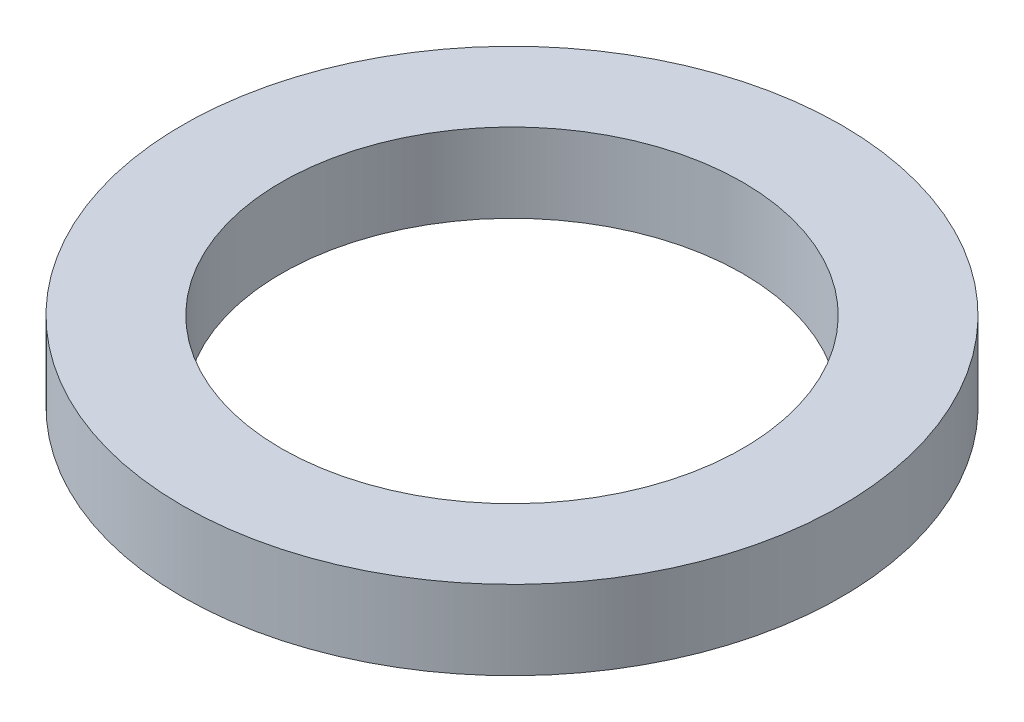
SolidWorks part; units mm, degrees
ref_plane "Alzado" through (0, 0, 0) normal (0, 0, 1) x (1, 0, 0)
ref_plane "Planta" through (0, 0, 0) normal (0, 1, 0) x (1, 0, 0)
ref_plane "Vista lateral" through (0, 0, 0) normal (1, 0, 0) x (0, 0, -1)
sketch "Croquis1" plane through (0, 0, 0) normal (0, 1, 0) x (1, 0, 0)
  circle A0 centre (0, 0) radius 1.75
  circle A1 centre (0, 0) radius 2.5
  dimension "D1" = 3.5
  dimension "D2" = 5
extrude "Saliente-Extruir1" add sketch "Croquis1" along normal blind 0.6
